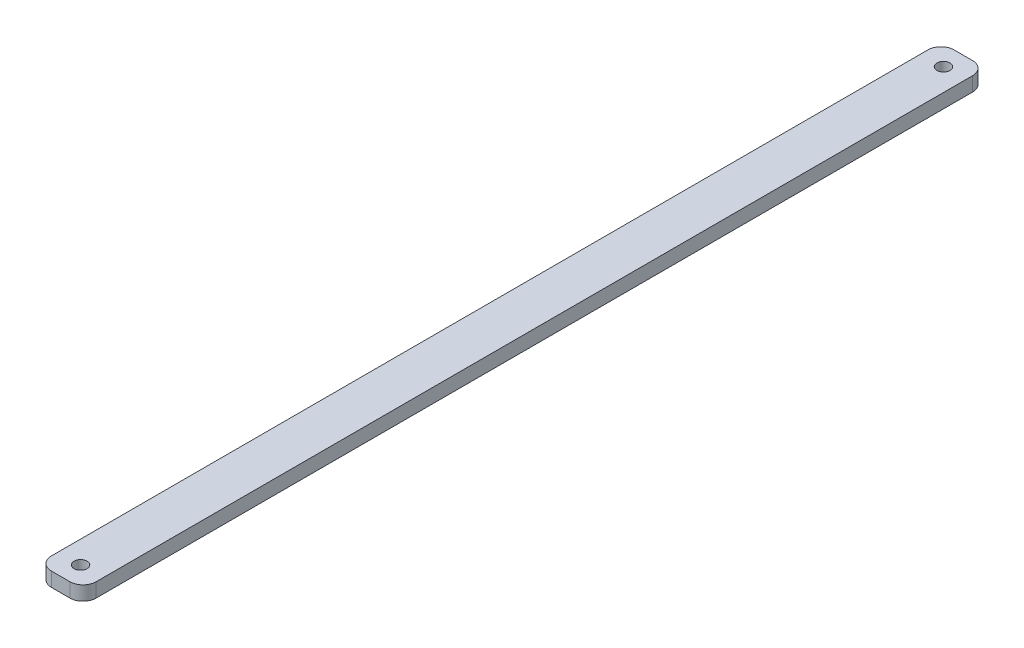
SolidWorks part; units mm, degrees
ref_plane "Front Plane" through (0, 0, 0) normal (0, 0, 1) x (1, 0, 0)
ref_plane "Top Plane" through (0, 0, 0) normal (0, 1, 0) x (1, 0, 0)
ref_plane "Right Plane" through (0, 0, 0) normal (1, 0, 0) x (0, 0, -1)
sketch "Sketch1" plane through (0, 0, 0) normal (0, 1, 0) x (1, 0, 0)
  line L0 (0, 96.52) -> (0, 0) construction
  line L1 (-5, 100.965) -> (5, 100.965)
  line L2 (-5, 100.965) -> (-5, -100.965)
  line L3 (-5, -100.965) -> (5, -100.965)
  line L4 (5, 100.965) -> (5, -100.965)
  line L5 (-5, 100.965) -> (5, -100.965) construction
  line L6 (-5, -100.965) -> (5, 100.965) construction
  line L7 (0, 0) -> (0, -96.52) construction
  circle A0 centre (0, 96.52) radius 1.4605
  circle A1 centre (0, -96.52) radius 1.4605
  point P0 (0, 0)
  dimension "D3" = 2.921
  dimension "D4" = 193.04
  dimension "D1" = 201.93
  dimension "D2" = 10
extrude "Boss-Extrude1" add sketch "Sketch1" along normal blind 3.175
fillet "Fillet1" radius 2.921 4 edges at (5, 1.5875, -100.965) (-5, 1.5875, -100.965) (5, 1.5875, 100.965) (-5, 1.5875, 100.965)
